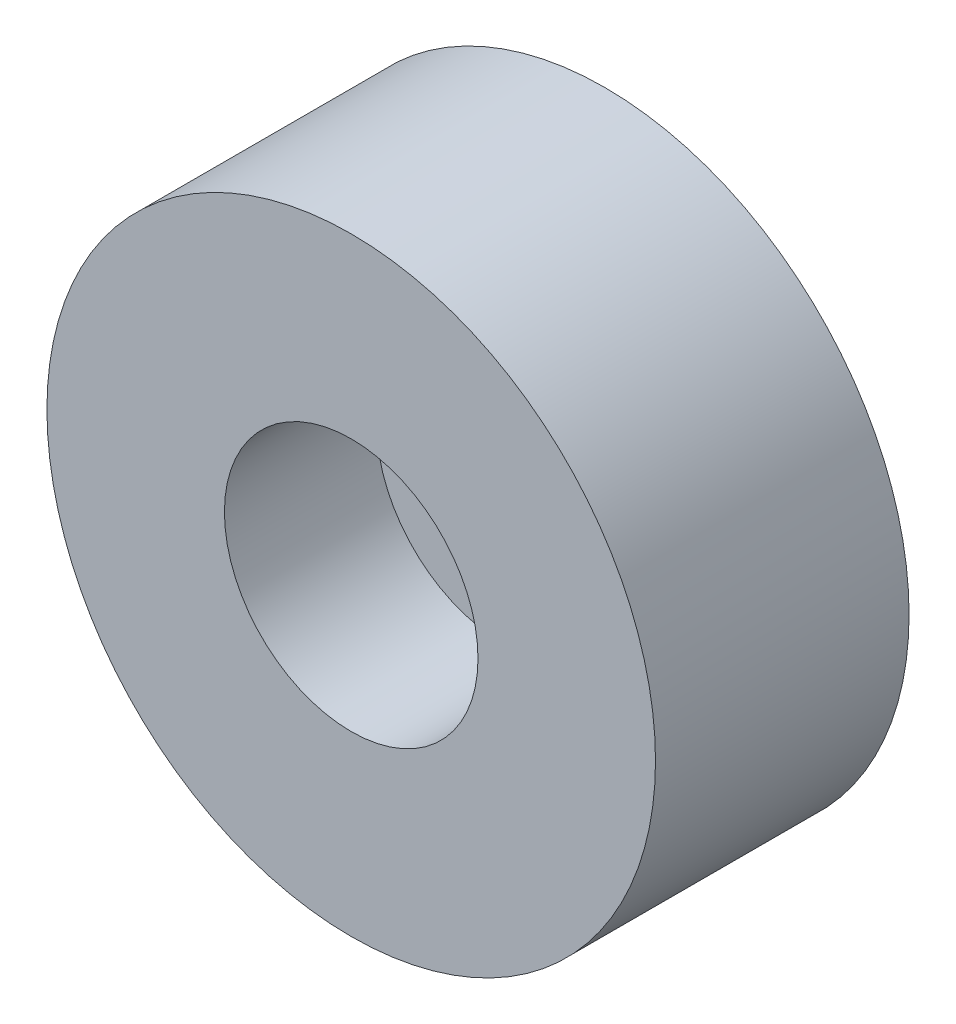
SolidWorks part; units mm, degrees
ref_plane "前视基准面" through (0, 0, 0) normal (0, 0, 1) x (1, 0, 0)
ref_plane "上视基准面" through (0, 0, 0) normal (0, 1, 0) x (1, 0, 0)
ref_plane "右视基准面" through (0, 0, 0) normal (1, 0, 0) x (0, 0, -1)
sketch "草图1" plane through (0, 0, 0) normal (0, 0, 1) x (1, 0, 0)
  circle A0 centre (0, 0) radius 6
  dimension "D1" = 12
extrude "凸台-拉伸1" add sketch "草图1" along normal blind 5
sketch "草图2" plane through (0, 0, 5) normal (0, 0, 1) x (1, 0, 0)
  circle A0 centre (0, 0) radius 2.5
  dimension "D1" = 5
extrude "切除-拉伸1" cut sketch "草图2" against normal blind 3
sketch "草图3" plane through (0, 0, 2) normal (0, 0, 1) x (1, 0, 0)
  circle A0 centre (0, 0) radius 1
  dimension "D1" = 2
extrude "切除-拉伸2" cut sketch "草图3" against normal blind 3
